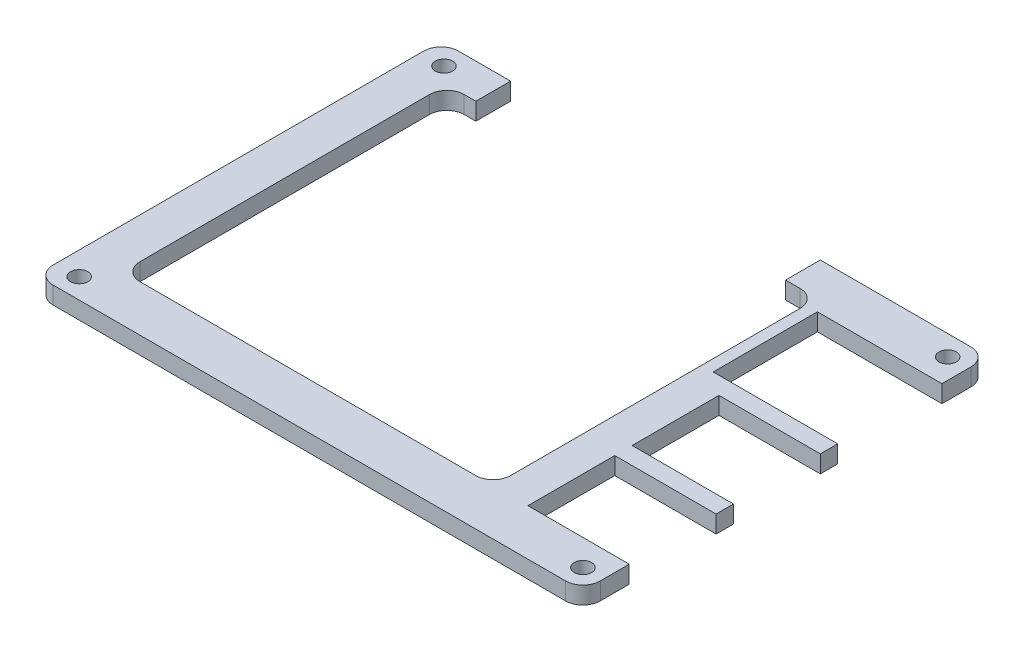
SolidWorks part; units mm, degrees
material "Acrylic (Medium-high impact)"
ref_plane "Front Plane" through (0, 0, 0) normal (0, 0, 1) x (1, 0, 0)
ref_plane "Top Plane" through (0, 0, 0) normal (0, 1, 0) x (1, 0, 0)
ref_plane "Right Plane" through (0, 0, 0) normal (1, 0, 0) x (0, 0, -1)
sketch "Sketch1" plane through (0, 0, 0) normal (0, 1, 0) x (1, 0, 0)
  line L1 (-47.25, 35) -> (47.25, 35)
  line L2 (-47.25, 35) -> (-47.25, -35)
  line L3 (-47.25, -35) -> (47.25, -35)
  line L4 (47.25, 35) -> (47.25, -35)
  line L5 (-47.25, 35) -> (47.25, -35) construction
  line L6 (-47.25, -35) -> (47.25, 35) construction
  point P0 (0, 0)
  dimension "D1" = 70
  dimension "D2" = 94.5
extrude "Boss-Extrude1" add sketch "Sketch1" along normal blind 3
sketch "Sketch3" plane through (0, 3, 0) normal (0, 1, 0) x (1, 0, 0)
  line L0 (47.25, -35) -> (47.25, 35) construction
  line L2 (47.25, 35) -> (-47.25, 35) construction
  circle A0 centre (43.75, 31.5) radius 1.5
  circle A1 centre (-43.25, 31.5) radius 1.5
  circle A2 centre (-43.25, -31.5) radius 1.5
  circle A3 centre (43.75, -31.5) radius 1.5
  dimension "D1" = 3
  dimension "D2" = 3.5
  dimension "D3" = 3.5
  dimension "D4" = 2
  dimension "D5" = 87
  dimension "D6" = 63
  dimension "D7" = 2
extrude "Cut-Extrude2" cut sketch "Sketch3" against normal through all
fillet "Fillet2" radius 3 4 edges at (-47.25, 1.5, 35) (-47.25, 1.5, -35) (47.25, 1.5, -35) (47.25, 1.5, 35)
sketch "Sketch5" plane through (0, 3, 0) normal (0, 1, 0) x (1, 0, 0)
  line L0 (-40.25, 29) -> (23.75, 29)
  line L1 (23.75, 29) -> (23.75, -27)
  line L2 (23.75, -27) -> (-40.25, -27)
  line L3 (-40.25, -27) -> (-40.25, 29)
  line L4 (47.25, 27) -> (25.75, 27)
  line L5 (47.25, -32) -> (47.25, 32) construction
  line L6 (25.75, 27) -> (25.75, 9)
  line L7 (25.75, 9) -> (47.25, 9)
  line L8 (47.25, 9) -> (47.25, 27)
  line L9 (47.25, 6) -> (29.75, 6)
  line L10 (29.75, 6) -> (29.75, -9)
  line L11 (29.75, -9) -> (47.25, -9)
  line L12 (47.25, -9) -> (47.25, 6)
  line L13 (47.25, -12) -> (29.75, -12)
  line L14 (29.75, -12) -> (29.75, -27)
  line L15 (29.75, -27) -> (47.25, -27)
  line L16 (47.25, -27) -> (47.25, -12)
  line L17 (44.25, 35) -> (-44.25, 35) construction
  line L18 (-47.25, 32) -> (-47.25, -32) construction
  line L19 (-35.25, 29) -> (-35.25, 35)
  line L20 (-35.25, 35) -> (18.25, 35)
  line L21 (18.25, 35) -> (18.25, 29)
  line M21 (47.25, -32) -> (47.25, 32)
  line M23 (44.25, 35) -> (-44.25, 35)
  dimension "D1" = 6
  dimension "D2" = 7
  dimension "D3" = 64
  dimension "D4" = 56
  dimension "D5" = 18
  dimension "D6" = 2
  dimension "D7" = 6
  dimension "D8" = 3
  dimension "D9" = 8
  dimension "D10" = 15
  dimension "D11" = 3
  dimension "D12" = 15
  dimension "D13" = 6
  dimension "D14" = 12
  dimension "D15" = 29
extrude "Cut-Extrude3" cut sketch "Sketch5" against normal through all contours L3 L2 L1 L0 | L21 L19 L0 M23 | L6 L7 L4 M21 | L10 L11 L9 M21 | L14 L15 L13 M21
fillet "Fillet3" radius 3 4 edges at (23.75, 1.5, -29) (23.75, 1.5, 27) (-40.25, 1.5, 27) (-40.25, 1.5, -29)
